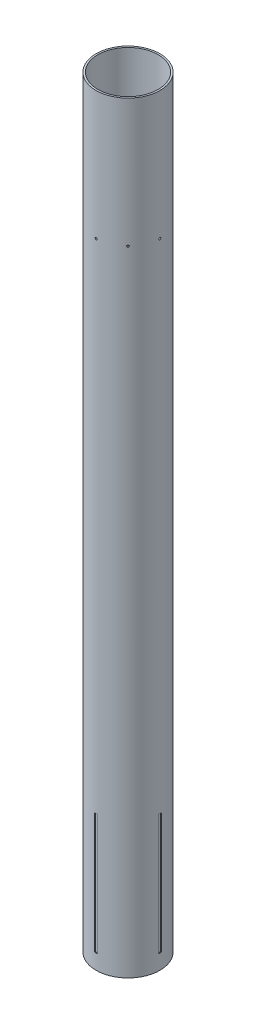
SolidWorks part; units mm, degrees
ref_plane "Front Plane" through (0, 0, 0) normal (0, 0, 1) x (1, 0, 0)
ref_plane "Top Plane" through (0, 0, 0) normal (0, 1, 0) x (1, 0, 0)
ref_plane "Right Plane" through (0, 0, 0) normal (1, 0, 0) x (0, 0, -1)
sketch "Sketch1" plane through (0, 0, 0) normal (0, 1, 0) x (1, 0, 0)
  circle A0 centre (0, 0) radius 53.721
  circle A1 centre (0, 0) radius 50.8
  dimension "D1" = 107.442
  dimension "D2" = 101.6
extrude "Tube Extrusion" add sketch "Sketch1" along normal blind 1282.7
ref_plane "Plane1" through (0, 0, 53.721) normal (0, 0, 1) x (1, 0, 0)
sketch "Sketch2" plane through (0, 0, 53.721) normal (0, 0, 1) x (1, 0, 0)
  line L0 (0, 1282.7) -> (0, 0) construction
  line L3 (53.721, 1282.7) -> (-53.721, 1282.7) construction
  circle A0 centre (0, 1066.8) radius 1.6383
  point P2 (0, 0)
  dimension "D1" = 3.2766
  dimension "D2" = 1066.8
extrude "Engine Block Hole" cut sketch "Sketch2" against normal up to next
pattern_circular "CirPattern1" count 8 over 360 about axis through (0, 1282.7, 0) along (0, -1, 0) of "Engine Block Hole"
sketch "Sketch3" plane through (0, 0, 53.721) normal (0, 0, 1) x (1, 0, 0)
  line L0 (0, 0) -> (0, 25.4) construction
  line L1 (-53.721, 0) -> (53.721, 0) construction
  line L3 (-2.667, 228.6) -> (2.667, 228.6)
  line L4 (-2.667, 228.6) -> (-2.667, 25.4)
  line L5 (-2.667, 25.4) -> (2.667, 25.4)
  line L6 (2.667, 228.6) -> (2.667, 25.4)
  point P8 (0, 25.4)
  dimension "D1" = 25.4
  dimension "D2" = 203.2
  dimension "D3" = 5.334
extrude "Fin Slots" cut sketch "Sketch3" against normal blind 1.27
pattern_circular "CirPattern2" count 4 over 360 about axis through (0, 0, 0) along (0, 1, 0) of "Fin Slots"
